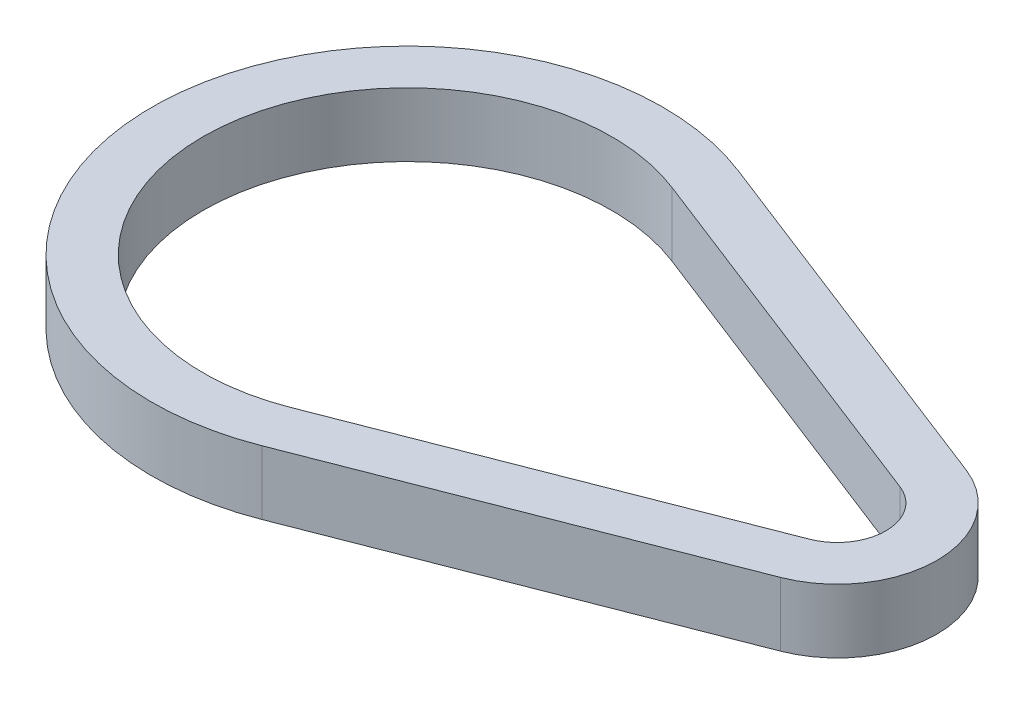
SolidWorks part; units mm, degrees
ref_plane "Front Plane" through (0, 0, 0) normal (0, 0, 1) x (1, 0, 0)
ref_plane "Top Plane" through (0, 0, 0) normal (0, 1, 0) x (1, 0, 0)
ref_plane "Right Plane" through (0, 0, 0) normal (1, 0, 0) x (0, 0, -1)
sketch "Sketch1" plane through (0, 0, 0) normal (0, 1, 0) x (1, 0, 0)
  line L0 (14.5065, 37.2768) -> (87.5453, 8.8532)
  line L2 (87.5453, -8.8532) -> (14.5065, -37.2768)
  arc A0 (14.5065, 37.2768) -> (14.5065, -37.2768) centre (0, 0) ccw
  arc A1 (87.5453, -8.8532) -> (87.5453, 8.8532) centre (84.1, 0) ccw
  dimension "D1" = 9.5
  dimension "D2" = 40
  dimension "D3" = 84.1
extrude "Extrude-Thin1" add sketch "Sketch1" along normal blind 12.5 thin thin type one direction wall 10
equation "\"12.5mmm\"=10"
